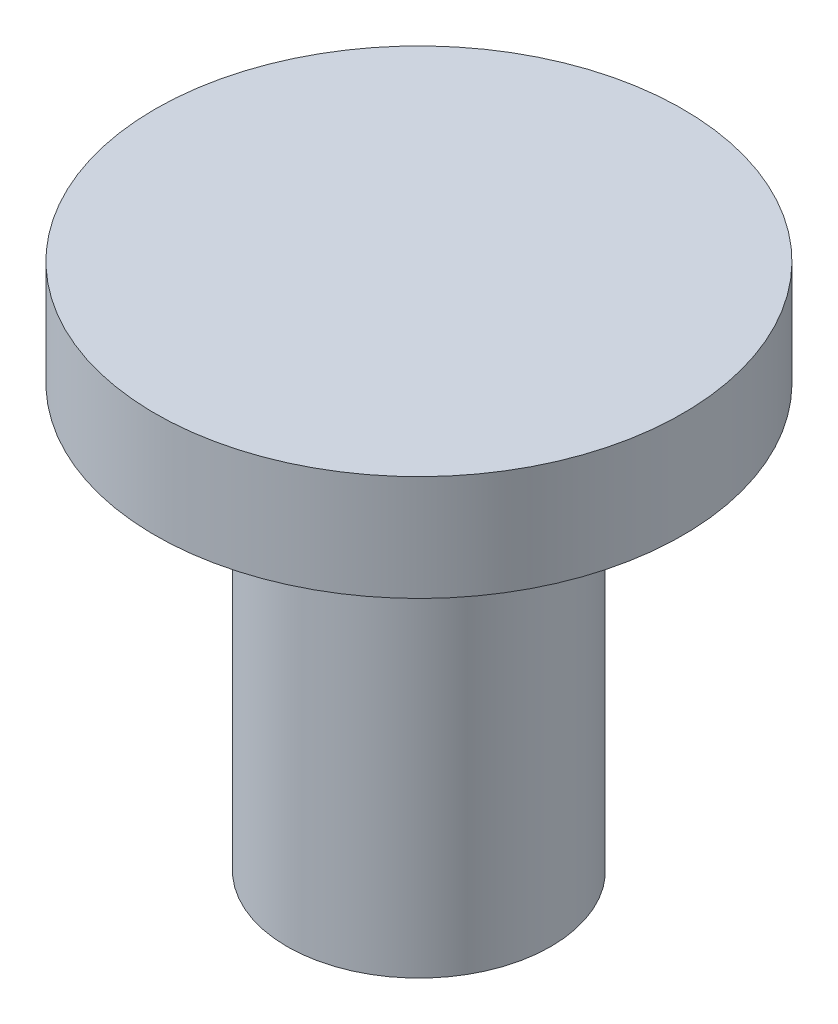
SolidWorks part; units mm, degrees
ref_plane "Front Plane" through (0, 0, 0) normal (0, 0, 1) x (1, 0, 0)
ref_plane "Top Plane" through (0, 0, 0) normal (0, 1, 0) x (1, 0, 0)
ref_plane "Right Plane" through (0, 0, 0) normal (1, 0, 0) x (0, 0, -1)
sketch "Sketch1" plane through (0, 0, 0) normal (0, 0, 1) x (1, 0, 0)
  line L0 (0, 0) -> (0, -6.35)
  line L1 (0, -6.35) -> (1.5875, -6.35)
  line L2 (1.5875, -6.35) -> (1.5875, -1.27)
  line L3 (1.5875, -1.27) -> (3.175, -1.27)
  line L4 (3.175, -1.27) -> (3.175, 0)
  line L5 (3.175, 0) -> (0, 0)
  dimension "D1" = 1.5875
  dimension "D2" = 5.08
  dimension "D3" = 1.27
  dimension "D4" = 3.175
revolve "Revolve1" add sketch "Sketch1" angle 360 about L0
